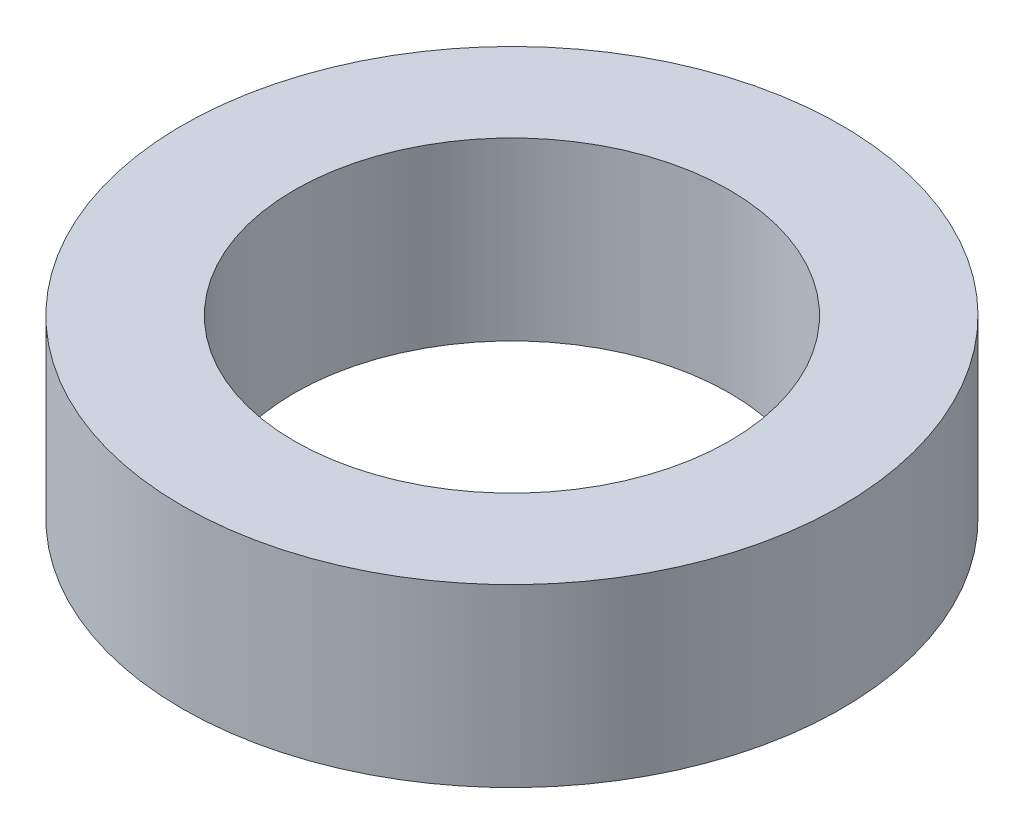
SolidWorks part; units mm, degrees
ref_plane "Front Plane" through (0, 0, 0) normal (0, 0, 1) x (1, 0, 0)
ref_plane "Top Plane" through (0, 0, 0) normal (0, 1, 0) x (1, 0, 0)
ref_plane "Right Plane" through (0, 0, 0) normal (1, 0, 0) x (0, 0, -1)
sketch "Sketch1" plane through (0, 0, 0) normal (0, 1, 0) x (1, 0, 0)
  circle A0 centre (0, 0) radius 7.5
  circle A1 centre (0, 0) radius 4.95
  dimension "D1" = 15
  dimension "D2" = 9.9
extrude "Boss-Extrude1" add sketch "Sketch1" along normal blind 4
